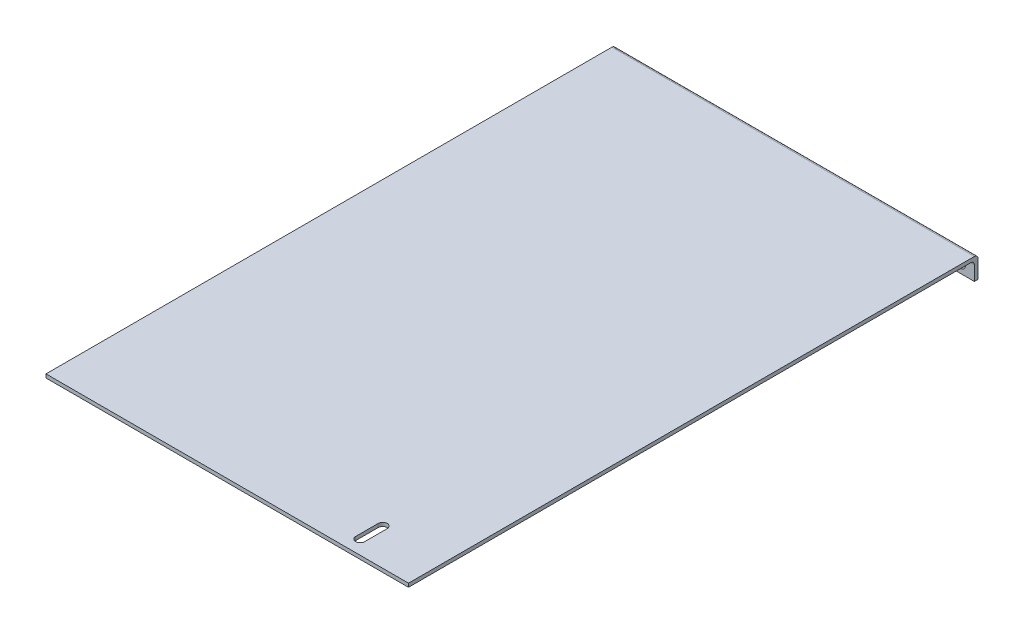
SolidWorks part; units mm, degrees
ref_plane "Front Plane" through (0, 0, 0) normal (0, 0, 1) x (1, 0, 0)
ref_plane "Top Plane" through (0, 0, 0) normal (0, 1, 0) x (1, 0, 0)
ref_plane "Right Plane" through (0, 0, 0) normal (1, 0, 0) x (0, 0, -1)
sketch "Sketch1" plane through (0, 0, 0) normal (1, 0, 0) x (0, 0, -1)
  line L2 (0, 0) -> (315, 0)
  line L3 (0, 0) -> (0, 2)
  line L4 (0, 2) -> (315, 2)
  line L5 (315, 0) -> (315, 2)
  dimension "D1" = 2
  dimension "D2" = 315
extrude "Boss-Extrude1" add sketch "Sketch1" along normal blind 200.5
sketch "Sketch16" plane through (0, 0, 0) normal (0, -1, 0) x (1, 0, 0)
  line L0 (200.5, -313) -> (0, -313)
  line L1 (200.5, 0) -> (200.5, -315) construction
  line L2 (0, -55) -> (0, 55) construction
  line L3 (200.5, -315) -> (0, -315) construction
  line L4 (200.5, -313) -> (200.5, -315)
  line L5 (200.5, -315) -> (0, -315)
  line L6 (0, -315) -> (0, -313)
  dimension "D1" = 2
extrude "Boss-Extrude2" add sketch "Sketch16" along normal blind 10
fillet "Fillet1" radius 2 1 edges at (100.25, 2, -315)
fillet "Fillet2" radius 2 1 edges at (100.25, 0, -313)
sketch "Sketch17" plane through (0, 0, -315) normal (0, 0, -1) x (-1, 0, 0)
  line L0 (-200.5, -5) -> (0, -5) construction
  line L1 (-200.5, -10) -> (-200.5, 0) construction
  line L2 (0, 6.6) -> (0, -6.6) construction
  circle A0 centre (-193, -5) radius 2.5
  circle A1 centre (-7.5, -5) radius 2.5
  dimension "D1" = 7.5
  dimension "D2" = 185.5
extrude "Cut-Extrude1" cut sketch "Sketch17" along direction (0, 0, -1) on the side against the normal blind 2
sketch "Sketch19" plane through (0, 2, 0) normal (0, 1, 0) x (1, 0, 0)
  line L0 (200.5, 313) -> (200.5, 0) construction
  line L1 (-6.6, 0) -> (6.6, 0) construction
  line L2 (168.5, 7.75) -> (168.5, 20.25)
  line L3 (163.5, 7.75) -> (163.5, 20.25)
  circle A0 centre (166, 7.75) radius 2.5
  circle A1 centre (166, 20.25) radius 2.5
  line M2 (200.5, 0) -> (200.5, 313)
  dimension "D1" = 34.5
  dimension "D3" = 12.5
  dimension "D2" = 7.75
extrude "Cut-Extrude2" cut sketch "Sketch19" along direction (0, 1, 0) on the side against the normal up to next (2 mm away) contours A1 L3 A0 L2 | A0 | A1 M2
